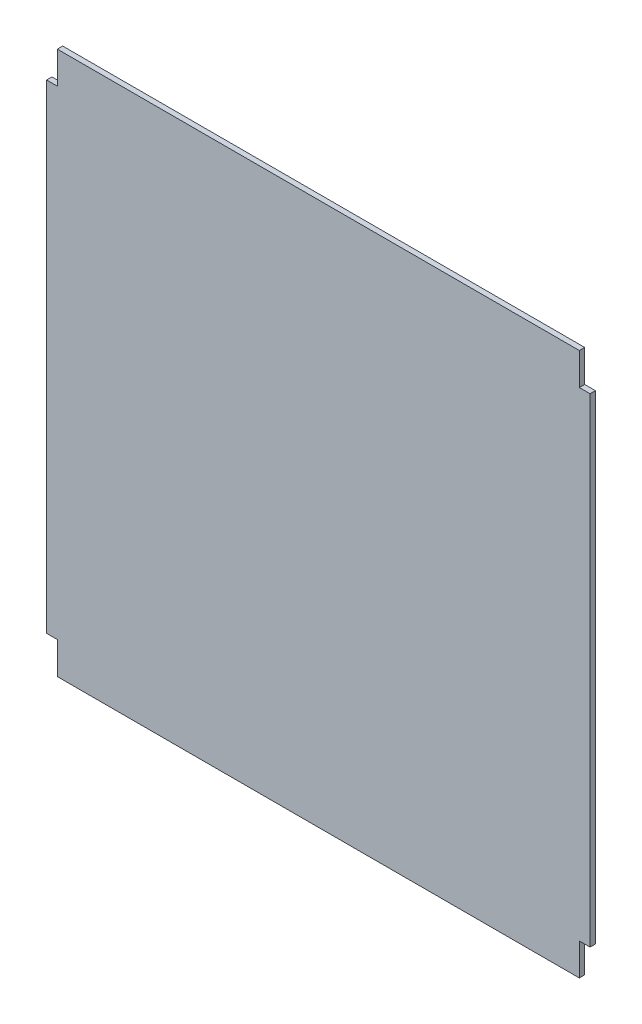
SolidWorks part; units mm, degrees
material "Teak"
ref_plane "Front Plane" through (0, 0, 0) normal (0, 0, 1) x (1, 0, 0)
ref_plane "Top Plane" through (0, 0, 0) normal (0, 1, 0) x (1, 0, 0)
ref_plane "Right Plane" through (0, 0, 0) normal (1, 0, 0) x (0, 0, -1)
sketch "Sketch1" plane through (0, 0, 0) normal (0, 0, 1) x (1, 0, 0)
  line L1 (0, 0) -> (-508, 0)
  line L2 (0, 0) -> (0, 508)
  line L3 (0, 508) -> (-508, 508)
  line L4 (-508, 0) -> (-508, 508)
  dimension "D1" = 508
  dimension "D2" = 508
extrude "Boss-Extrude1" add sketch "Sketch1" along normal blind 4 contours L3 L4 L1 L2
ref_plane "Plane1" through (0, 508, 4) normal (0, 1, 0) x (1, 0, 0)
sketch "Sketch3" plane through (0, 0, 4) normal (0, 0, 1) x (1, 0, 0)
  line L0 (0, 508) -> (-508, 508) construction
  line L1 (-50.8, 457.2) -> (-457.2, 457.2)
  line L2 (-50.8, 457.2) -> (-50.8, 50.8)
  line L3 (-50.8, 50.8) -> (-457.2, 50.8)
  line L4 (-457.2, 457.2) -> (-457.2, 50.8)
  line L5 (-508, 0) -> (-508, 508) construction
  line L6 (0, 0) -> (0, 508) construction
  line L7 (0, 0) -> (-508, 0) construction
  dimension "D1" = 50.8
  dimension "D2" = 50.8
  dimension "D3" = 50.8
  dimension "D4" = 50.8
extrude "Cut-Extrude1" cut sketch "Sketch3" against normal blind 4
sketch "Sketch4" plane through (0, 0, 4) normal (0, 0, 1) x (1, 0, 0)
  line L1 (-508, 508) -> (0, 508)
  line L2 (-508, 508) -> (-508, 0)
  line L3 (-508, 0) -> (0, 0)
  line L4 (0, 508) -> (0, 0)
extrude "Boss-Extrude2" add sketch "Sketch4" along normal blind 1
sketch "Sketch5" plane through (0, 0, 0) normal (0, 0, -1) x (-1, 0, 0)
  line L1 (0, 508) -> (10, 508)
  line L2 (0, 508) -> (0, 478)
  line L3 (0, 478) -> (10, 478)
  line L4 (10, 508) -> (10, 478)
  line L5 (508, 508) -> (498, 508)
  line L6 (508, 508) -> (508, 478)
  line L7 (508, 478) -> (498, 478)
  line L8 (498, 508) -> (498, 478)
  line L9 (508, 0) -> (498, 0)
  line L10 (508, 0) -> (508, 30)
  line L11 (508, 30) -> (498, 30)
  line L12 (498, 0) -> (498, 30)
  line L13 (0, 0) -> (10, 0)
  line L14 (0, 0) -> (0, 30)
  line L15 (0, 30) -> (10, 30)
  line L16 (10, 0) -> (10, 30)
  dimension "D1" = 10
  dimension "D2" = 30
  dimension "D3" = 10
  dimension "D4" = 30
  dimension "D5" = 30
  dimension "D6" = 10
  dimension "D7" = 30
  dimension "D8" = 10
extrude "Cut-Extrude2" cut sketch "Sketch5" against normal blind 5
